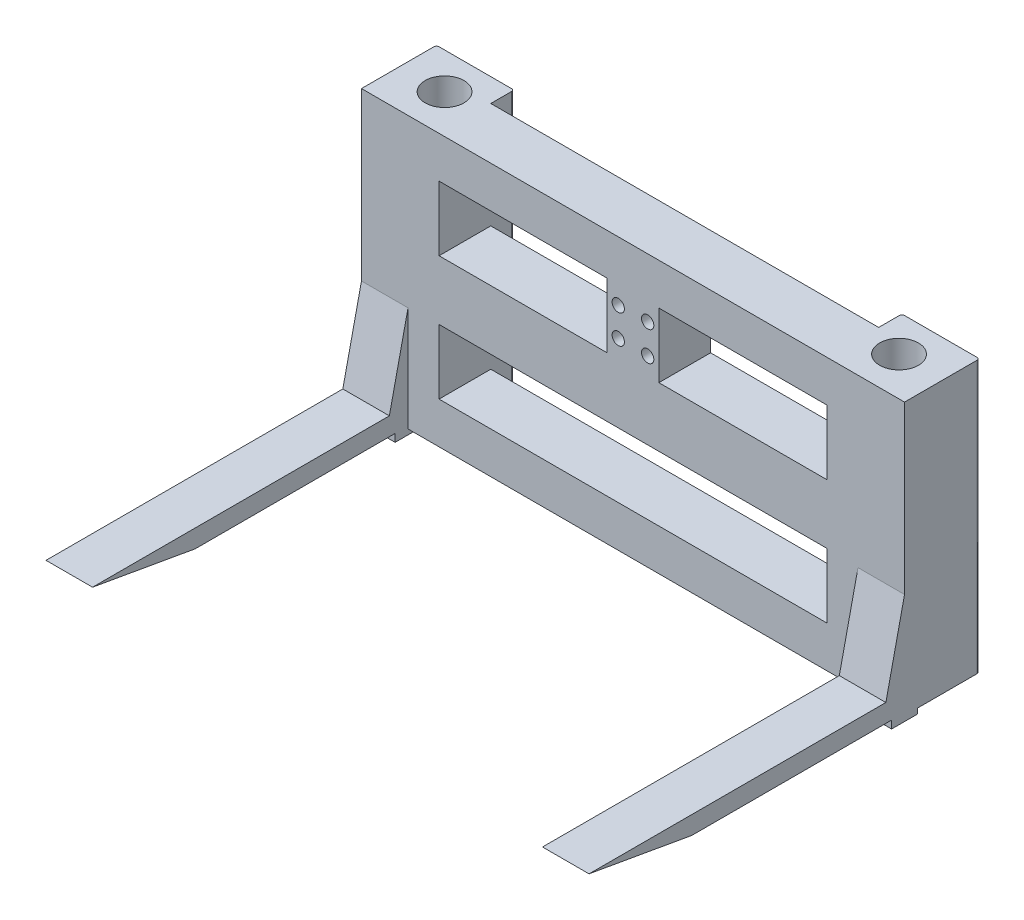
SolidWorks part; units mm, degrees
material "PVC Rigid"
ref_plane "Front Plane" through (0, 0, 0) normal (0, 0, 1) x (1, 0, 0)
ref_plane "Top Plane" through (0, 0, 0) normal (0, 1, 0) x (1, 0, 0)
ref_plane "Right Plane" through (0, 0, 0) normal (1, 0, 0) x (0, 0, -1)
sketch "Sketch1" plane through (0, 0, 0) normal (0, 0, 1) x (1, 0, 0)
  line L0 (4.8837, 71.8403) -> (4.8837, -82.4193) construction
  line L1 (-100.1163, 45.9884) -> (109.8837, 45.9884)
  line L2 (-100.1163, 45.9884) -> (-100.1163, -59.0116)
  line L3 (-100.1163, -59.0116) -> (109.8837, -59.0116)
  line L4 (109.8837, 45.9884) -> (109.8837, -59.0116)
  dimension "D1" = 210
  dimension "D2" = 105
extrude "Boss-Extrude1" add sketch "Sketch1" along normal blind 20
sketch "Sketch3" plane through (0, 0, 20) normal (0, 0, 1) x (1, 0, 0)
  line L0 (-100.1163, -59.0116) -> (109.8837, -59.0116) construction
  line L1 (-82.1163, -59.0116) -> (-100.1163, -59.0116)
  line L2 (-82.1163, -59.0116) -> (-82.1163, -41.0116)
  line L3 (-82.1163, -41.0116) -> (-100.1163, -41.0116)
  line L4 (-100.1163, -59.0116) -> (-100.1163, -41.0116)
  line L5 (-82.1163, -59.0116) -> (-100.1163, -41.0116) construction
  line L6 (-82.1163, -41.0116) -> (-100.1163, -59.0116) construction
  line L7 (-100.1163, 45.9884) -> (-100.1163, -59.0116) construction
  line L13 (4.8837, -59.0116) -> (4.8837, -22.3349) construction
  line L14 (91.8837, -41.0116) -> (109.8837, -59.0116) construction
  line L15 (91.8837, -59.0116) -> (109.8837, -41.0116) construction
  line L16 (109.8837, -59.0116) -> (109.8837, -41.0116)
  line L17 (91.8837, -41.0116) -> (109.8837, -41.0116)
  line L18 (91.8837, -59.0116) -> (91.8837, -41.0116)
  line L19 (91.8837, -59.0116) -> (109.8837, -59.0116)
  point P0 (-91.1163, -50.0116)
  point P15 (100.8837, -50.0116)
  dimension "D1" = 18
  dimension "D2" = 18
extrude "Cut-Extrude1" cut sketch "Sketch3" against normal blind 5
sketch "Sketch6" plane through (0, 0, 15) normal (0, 0, 1) x (1, 0, 0)
  line L1 (-100.1163, -41.0116) -> (-82.1163, -41.0116)
  line L2 (-100.1163, -41.0116) -> (-100.1163, -61.0116)
  line L3 (-100.1163, -61.0116) -> (-82.1163, -61.0116)
  line L4 (-82.1163, -41.0116) -> (-82.1163, -61.0116)
  line L9 (4.8837, -59.0116) -> (4.8837, -35.9973) construction
  line L10 (-82.1163, -59.0116) -> (91.8837, -59.0116) construction
  line L11 (91.8837, -41.0116) -> (91.8837, -61.0116)
  line L12 (109.8837, -61.0116) -> (91.8837, -61.0116)
  line L13 (109.8837, -41.0116) -> (109.8837, -61.0116)
  line L14 (109.8837, -41.0116) -> (91.8837, -41.0116)
  dimension "D1" = 18
  dimension "D2" = 20
extrude "Boss-Extrude2" add sketch "Sketch6" along normal blind 10
sketch "Sketch7" plane through (0, 0, 25) normal (0, 0, 1) x (1, 0, 0)
  line L0 (-100.1163, -41.0116) -> (-100.1163, -61.0116) construction
  line L1 (-100.1163, -51.0116) -> (-82.1163, -51.0116)
  line L2 (-100.1163, -51.0116) -> (-100.1163, -58.0116)
  line L3 (-100.1163, -58.0116) -> (-82.1163, -58.0116)
  line L4 (-82.1163, -51.0116) -> (-82.1163, -58.0116)
  line L5 (-82.1163, -61.0116) -> (-82.1163, -41.0116) construction
  line L12 (4.8837, -59.0116) -> (4.8837, -38.3942) construction
  line L13 (-82.1163, -59.0116) -> (91.8837, -59.0116) construction
  line L14 (91.8837, -51.0116) -> (91.8837, -58.0116)
  line L15 (109.8837, -58.0116) -> (91.8837, -58.0116)
  line L16 (109.8837, -51.0116) -> (109.8837, -58.0116)
  line L17 (109.8837, -51.0116) -> (91.8837, -51.0116)
  dimension "D1" = 7
extrude "Cut-Extrude2" cut sketch "Sketch7" against normal blind 3
sketch "Sketch8" plane through (0, 0, 22) normal (0, 0, 1) x (1, 0, 0)
  line L0 (4.8837, -59.0116) -> (4.8837, -41.4055) construction
  line L1 (-100.1163, -51.0116) -> (-82.1163, -51.0116)
  line L2 (-100.1163, -51.0116) -> (-100.1163, -58.0116)
  line L3 (-100.1163, -58.0116) -> (-82.1163, -58.0116)
  line L4 (-82.1163, -51.0116) -> (-82.1163, -58.0116)
  line L9 (-82.1163, -59.0116) -> (91.8837, -59.0116) construction
  line L10 (91.8837, -51.0116) -> (91.8837, -58.0116)
  line L11 (109.8837, -58.0116) -> (91.8837, -58.0116)
  line L12 (109.8837, -51.0116) -> (109.8837, -58.0116)
  line L13 (109.8837, -51.0116) -> (91.8837, -51.0116)
extrude "Boss-Extrude3" add sketch "Sketch8" along normal blind 120
sketch "Sketch9" plane through (109.8837, 0, 0) normal (1, 0, 0) x (0, 0, -1)
  line L0 (-142, -51.0116) -> (-102.301, -58.0116)
  line L2 (-142, -58.0116) -> (-25, -58.0116) construction
  dimension "D1" = 10
extrude "Cut-Extrude4" cut sketch "Sketch9" against normal through all both and the other way through all flip side to cut
sketch "Sketch12" plane through (0, 0, 20) normal (0, 0, 1) x (1, 0, 0)
  line L0 (109.8837, -41.0116) -> (109.8837, 45.9884) construction
  line L1 (79.8837, 4.9884) -> (-70.1163, 4.9884)
  line L2 (79.8837, 4.9884) -> (79.8837, 29.9884)
  line L3 (79.8837, 29.9884) -> (-70.1163, 29.9884)
  line L4 (-70.1163, 4.9884) -> (-70.1163, 29.9884)
  line L5 (79.8837, 4.9884) -> (-70.1163, 29.9884) construction
  line L6 (79.8837, 29.9884) -> (-70.1163, 4.9884) construction
  line L7 (79.8837, -43.0116) -> (-70.1163, -43.0116)
  line L8 (79.8837, -43.0116) -> (79.8837, -18.0116)
  line L9 (79.8837, -18.0116) -> (-70.1163, -18.0116)
  line L10 (-70.1163, -43.0116) -> (-70.1163, -18.0116)
  line L11 (79.8837, -43.0116) -> (-70.1163, -18.0116) construction
  line L12 (79.8837, -18.0116) -> (-70.1163, -43.0116) construction
  line L13 (-82.1163, -59.0116) -> (91.8837, -59.0116) construction
  line L14 (109.8837, 45.9884) -> (-100.1163, 45.9884) construction
  point P0 (4.8837, 17.4884)
  point P5 (4.8837, -30.5116)
  dimension "D1" = 16
  dimension "D2" = 16
  dimension "D3" = 25
  dimension "D4" = 25
  dimension "D5" = 150
  dimension "D6" = 150
  dimension "D7" = 30
  dimension "D8" = 30
extrude "Cut-Extrude5" cut sketch "Sketch12" against normal through all
sketch "Sketch15" plane through (0, 45.9884, 0) normal (0, 1, 0) x (1, 0, 0)
  line L1 (-100.1163, 0) -> (-70.1163, 0)
  line L2 (-100.1163, 0) -> (-100.1163, 9)
  line L3 (-100.1163, 9) -> (-70.1163, 9)
  line L4 (-70.1163, 0) -> (-70.1163, 9)
  line L5 (109.8837, 0) -> (79.8837, 0)
  line L6 (109.8837, 0) -> (109.8837, 9)
  line L7 (109.8837, 9) -> (79.8837, 9)
  line L8 (79.8837, 0) -> (79.8837, 9)
  dimension "D1" = 30
  dimension "D2" = 9
  dimension "D3" = 30
extrude "Boss-Extrude4" add sketch "Sketch15" against normal up to surface (105 mm away) up to face at (4.8837, -59.0116, 12.5)
sketch "Sketch16" plane through (0, 45.9884, 0) normal (0, 1, 0) x (1, 0, 0)
  line L10 (4.8837, 0) -> (4.8837, -109.9152) construction
  line L11 (79.8837, 0) -> (-70.1163, 0) construction
  circle A2 centre (-82.9913, -5) radius 7.5
  circle A3 centre (92.7587, -5) radius 7.5
  point P0 (-87.6163, 4.5)
  dimension "D1" = 15
  dimension "D2" = 87.875
extrude "Cut-Extrude11" cut sketch "Sketch16" against normal up to surface (105 mm away) up to face at (4.8837, -59.0116, 5.3333)
sketch "Sketch20" plane through (0, 0, 20) normal (0, 0, 1) x (1, 0, 0)
  line L0 (79.8837, 29.9884) -> (-70.1163, 29.9884) construction
  line L1 (-5.1163, 29.9884) -> (14.8837, 29.9884)
  line L2 (-5.1163, 29.9884) -> (-5.1163, 4.9884)
  line L3 (-5.1163, 4.9884) -> (14.8837, 4.9884)
  line L4 (14.8837, 29.9884) -> (14.8837, 4.9884)
  line L5 (-70.1163, 4.9884) -> (79.8837, 4.9884) construction
extrude "Boss-Extrude5" add sketch "Sketch20" against normal up to surface (20 mm away) up to face at (4.8837, 37.9884, 0)
sketch "Sketch21" plane through (0, 0, 20) normal (0, 0, 1) x (1, 0, 0)
  line L0 (-5.1163, 17.4884) -> (14.8837, 17.4884) construction
  line L1 (-5.1163, 29.9884) -> (-5.1163, 4.9884) construction
  line L2 (14.8837, 4.9884) -> (14.8837, 29.9884) construction
  line L3 (4.8837, 45.9884) -> (4.8837, 0) construction
  line L4 (109.8837, 45.9884) -> (-100.1163, 45.9884) construction
  circle A0 centre (-0.8188, 11.9384) radius 2.375
  circle A1 centre (10.5562, 11.7884) radius 2.375
  circle A2 centre (10.5562, 23.1884) radius 2.375
  circle A3 centre (-0.8188, 23.0384) radius 2.375
  dimension "D1" = 5.7025
  dimension "D2" = 5.6725
  dimension "D5" = 4.75
  dimension "D6" = 4.75
  dimension "D3" = 5.55
  dimension "D4" = 5.7
extrude "Cut-Extrude9" cut sketch "Sketch21" against normal up to vertex (20 mm away) up to point (0, 0, 0)
fillet "Fillet1" radius 1 4 edges at (-100.1163, -6.5116, -9) (-70.1163, -6.5116, -9) (79.8837, -6.5116, -9) (109.8837, -6.5116, -9)
sketch "Sketch23" plane through (-100.1163, 0, 0) normal (-1, 0, 0) x (0, 0, 1)
  line L0 (20, -18.4612) -> (27.2173, -51.0116)
  line L1 (20, 45.9884) -> (20, -41.0116) construction
  line L2 (142, -51.0116) -> (25, -51.0116) construction
  line L3 (27.2173, -51.0116) -> (20, -51.0116)
  line L4 (20, -51.0116) -> (20, -18.4612)
extrude "Boss-Extrude6" add sketch "Sketch23" against normal up to surface (18 mm away) up to face at (-82.1163, -54.0116, 41.4301)
sketch "Sketch25" plane through (109.8837, 0, 0) normal (1, 0, 0) x (0, 0, -1)
  line L0 (-20, -18.4612) -> (-27.2173, -51.0116)
  line L1 (-27.2173, -51.0116) -> (-20, -51.0116)
  line L2 (-20, -51.0116) -> (-20, -18.4612)
extrude "Boss-Extrude7" add sketch "Sketch25" against normal up to surface (18 mm away) up to face at (91.8837, -54.0116, 41.4301)
sketch "Sketch26" plane through (0, 0, 20) normal (0, 0, 1) x (1, 0, 0)
  line L0 (14.8837, 4.9884) -> (14.8837, 29.9884) construction
  line L1 (-5.1163, 29.9884) -> (-5.1163, 4.9884) construction
  line L2 (14.8837, 4.9884) -> (14.8837, 29.9884)
  line L3 (-5.1163, 29.9884) -> (-5.1163, 4.9884)
  line L4 (-5.1163, 29.9884) -> (14.8837, 29.9884)
  line L5 (14.8837, 4.9884) -> (-5.1163, 4.9884)
  circle A0 centre (-0.8188, 11.9384) radius 2.375 construction
  circle A1 centre (10.5562, 11.7884) radius 2.375 construction
  circle A2 centre (10.5562, 23.1884) radius 2.375 construction
  circle A3 centre (-0.8188, 23.0384) radius 2.375 construction
  circle A4 centre (-0.8188, 11.9384) radius 2.375
  circle A5 centre (10.5562, 11.7884) radius 2.375
  circle A6 centre (10.5562, 23.1884) radius 2.375
  circle A7 centre (-0.8188, 23.0384) radius 2.375
  dimension "D1" = 6.8
  dimension "D2" = 4.3275
  dimension "D3" = 4.2975
  dimension "D4" = 6.95
  dimension "D5" = 11.375
  dimension "D6" = 11.375
  dimension "D7" = 6.8
scale "Scale1" scale about centroid uniform scaling yes scale factor 0.4
